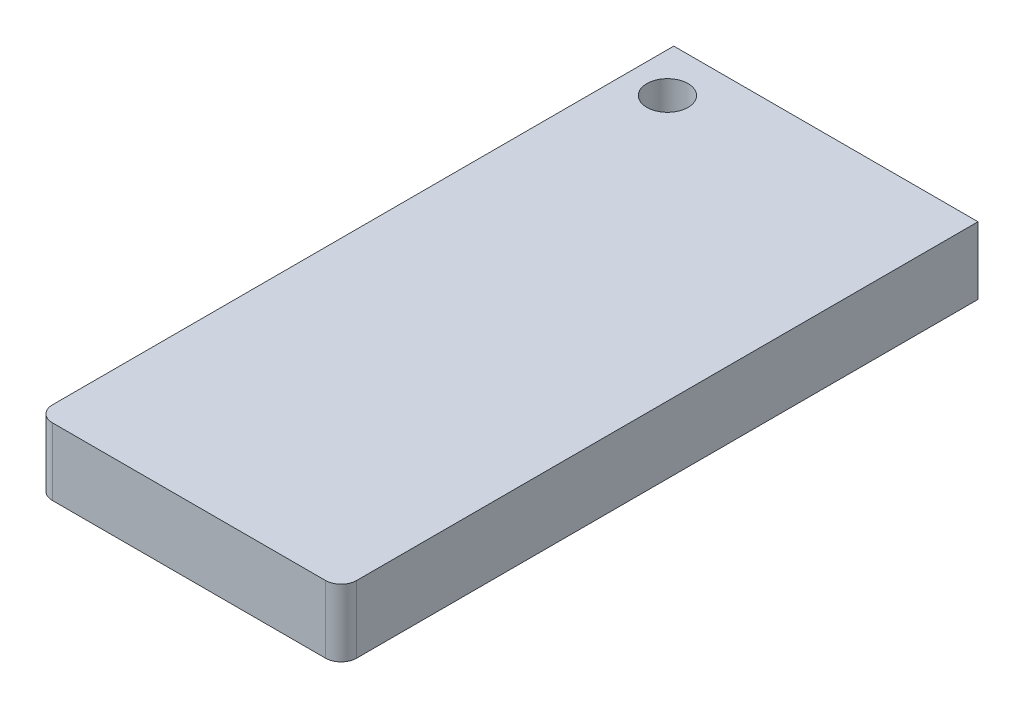
SolidWorks part; units mm, degrees
ref_plane "Front Plane" through (0, 0, 0) normal (0, 0, 1) x (1, 0, 0)
ref_plane "Top Plane" through (0, 0, 0) normal (0, 1, 0) x (1, 0, 0)
ref_plane "Right Plane" through (0, 0, 0) normal (1, 0, 0) x (0, 0, -1)
sketch "Sketch1" plane through (0, 0, 0) normal (0, 1, 0) x (1, 0, 0)
  line L1 (-26.375, -61.5) -> (26.375, -61.5)
  line L2 (-29.375, -58.5) -> (-29.375, 61.5)
  line L3 (-29.375, 61.5) -> (29.375, 61.5)
  line L4 (29.375, -58.5) -> (29.375, 61.5)
  line L5 (-29.375, -61.5) -> (29.375, 61.5) construction
  line L6 (-29.375, 61.5) -> (29.375, -61.5) construction
  arc A0 (-26.375, -61.5) -> (-29.375, -58.5) centre (-26.375, -58.5) cw
  arc A1 (26.375, -61.5) -> (29.375, -58.5) centre (26.375, -58.5) ccw
  point P0 (0, 0)
  dimension "D3" = 3
  dimension "D1" = 58.75
  dimension "D2" = 120
extrude "Boss-Extrude1" add sketch "Sketch1" along normal blind 13
sketch "Sketch2" plane through (0, 13, 0) normal (0, 1, 0) x (1, 0, 0)
  circle A0 centre (-21.7248, 52.6252) radius 3.9848
extrude "Cut-Extrude1" cut sketch "Sketch2" against normal through all
